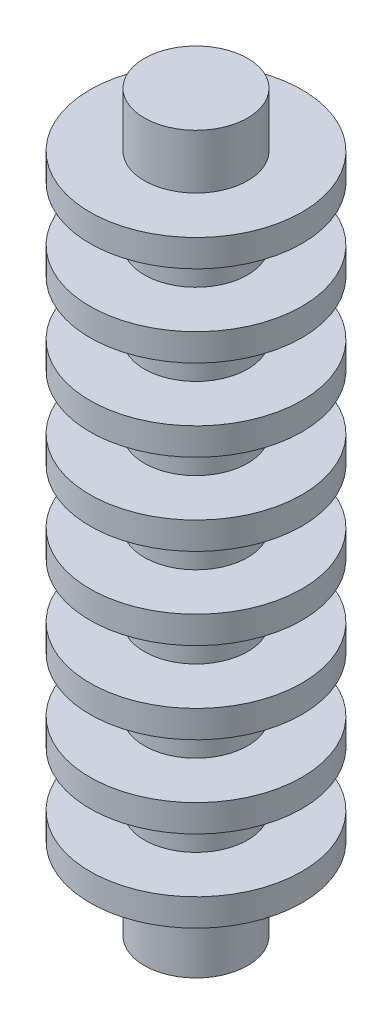
SolidWorks part; units mm, degrees
ref_plane "Front Plane" through (0, 0, 0) normal (0, 0, 1) x (1, 0, 0)
ref_plane "Top Plane" through (0, 0, 0) normal (0, 1, 0) x (1, 0, 0)
ref_plane "Right Plane" through (0, 0, 0) normal (1, 0, 0) x (0, 0, -1)
sketch "Sketch1" plane through (0, 0, 0) normal (0, 0, 1) x (1, 0, 0)
  line L0 (0, -24) -> (0, 24) construction
  line L1 (3.8, 24) -> (3.8, 23)
  line L2 (-19.9325, 24) -> (3.8, 24) construction
  line L3 (3.8, 18) -> (3.8, 17)
  line L4 (3.8, 17) -> (7.8, 17)
  line L5 (3.8, 23) -> (7.8, 23)
  line L6 (7.8, 23) -> (7.8, 21)
  line L7 (7.8, 21) -> (3.8, 21)
  line L8 (3.8, 21) -> (3.8, 18)
  line L9 (3.8, 24) -> (3.8, 27)
  line L10 (3.8, 27) -> (0, 27)
  line L11 (3.8, -24) -> (3.8, -27)
  line L12 (3.8, -27) -> (0, -27)
  line L13 (7.8, 17) -> (7.8, 15)
  line L14 (7.8, 15) -> (3.8, 15)
  line L15 (3.8, 15) -> (3.8, 12)
  line L16 (0, 27) -> (0, -27)
  line L20 (3.8, 12) -> (3.8, 11)
  line L21 (3.8, 11) -> (7.8, 11)
  line L22 (7.8, 11) -> (7.8, 9)
  line L23 (7.8, 9) -> (3.8, 9)
  line L24 (3.8, 9) -> (3.8, 6)
  line L29 (3.8, 6) -> (3.8, 5)
  line L30 (3.8, 5) -> (7.8, 5)
  line L31 (7.8, 5) -> (7.8, 3)
  line L32 (7.8, 3) -> (3.8, 3)
  line L33 (3.8, 3) -> (3.8, 0)
  line L38 (3.8, 0) -> (3.8, -1)
  line L39 (3.8, -1) -> (7.8, -1)
  line L40 (7.8, -1) -> (7.8, -3)
  line L41 (7.8, -3) -> (3.8, -3)
  line L42 (3.8, -3) -> (3.8, -6)
  line L47 (3.8, -6) -> (3.8, -7)
  line L48 (3.8, -7) -> (7.8, -7)
  line L49 (7.8, -7) -> (7.8, -9)
  line L50 (7.8, -9) -> (3.8, -9)
  line L51 (3.8, -9) -> (3.8, -12)
  line L56 (3.8, -12) -> (3.8, -13)
  line L57 (3.8, -13) -> (7.8, -13)
  line L58 (7.8, -13) -> (7.8, -15)
  line L59 (7.8, -15) -> (3.8, -15)
  line L60 (3.8, -15) -> (3.8, -18)
  line L65 (3.8, -18) -> (3.8, -19)
  line L66 (3.8, -19) -> (7.8, -19)
  line L67 (7.8, -19) -> (7.8, -21)
  line L68 (7.8, -21) -> (3.8, -21)
  line L69 (3.8, -21) -> (3.8, -24)
  point P4 (0, 0)
  dimension "D1" = 48
  dimension "D2" = 3.8
  dimension "D3" = 3
  dimension "D4" = 3
  dimension "D7" = 2
  dimension "D11" = 4
  dimension "D12" = 8
revolve "Revolve1" add sketch "Sketch1" angle 360 about L16
